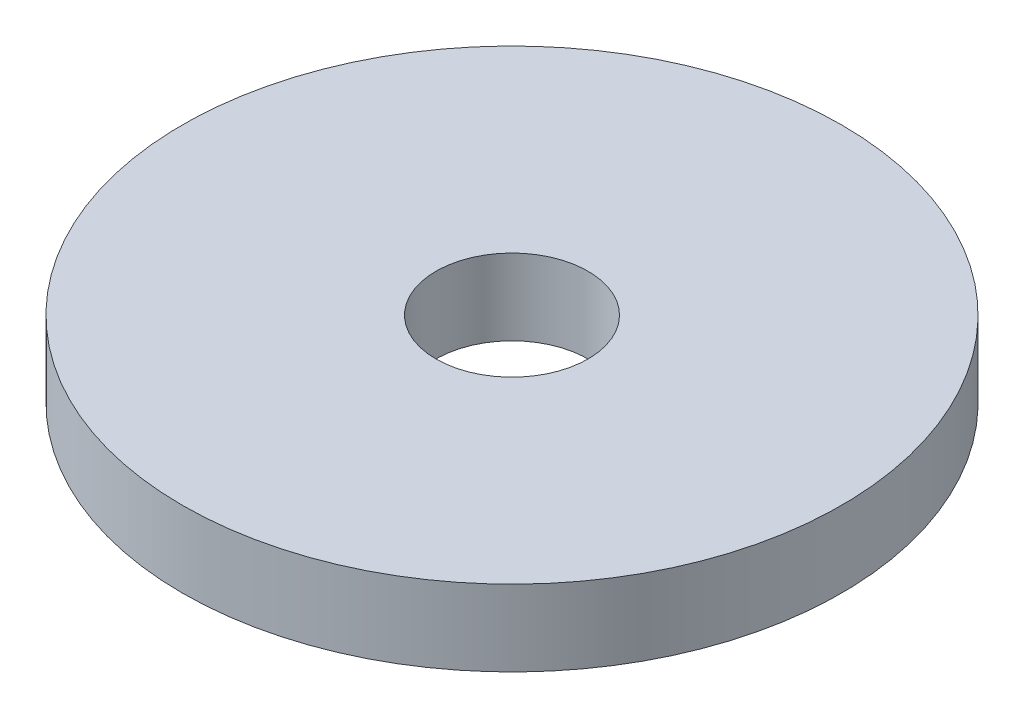
SolidWorks part; units mm, degrees
ref_plane "Front Plane" through (0, 0, 0) normal (0, 0, 1) x (1, 0, 0)
ref_plane "Top Plane" through (0, 0, 0) normal (0, 1, 0) x (1, 0, 0)
ref_plane "Right Plane" through (0, 0, 0) normal (1, 0, 0) x (0, 0, -1)
sketch "Sketch1" plane through (0, 0, 0) normal (0, 1, 0) x (1, 0, 0)
  circle A0 centre (0, 0) radius 3
  circle A1 centre (0, 0) radius 13
  dimension "D1" = 26
  dimension "D2" = 6
extrude "Boss-Extrude1" add sketch "Sketch1" along normal blind 3
